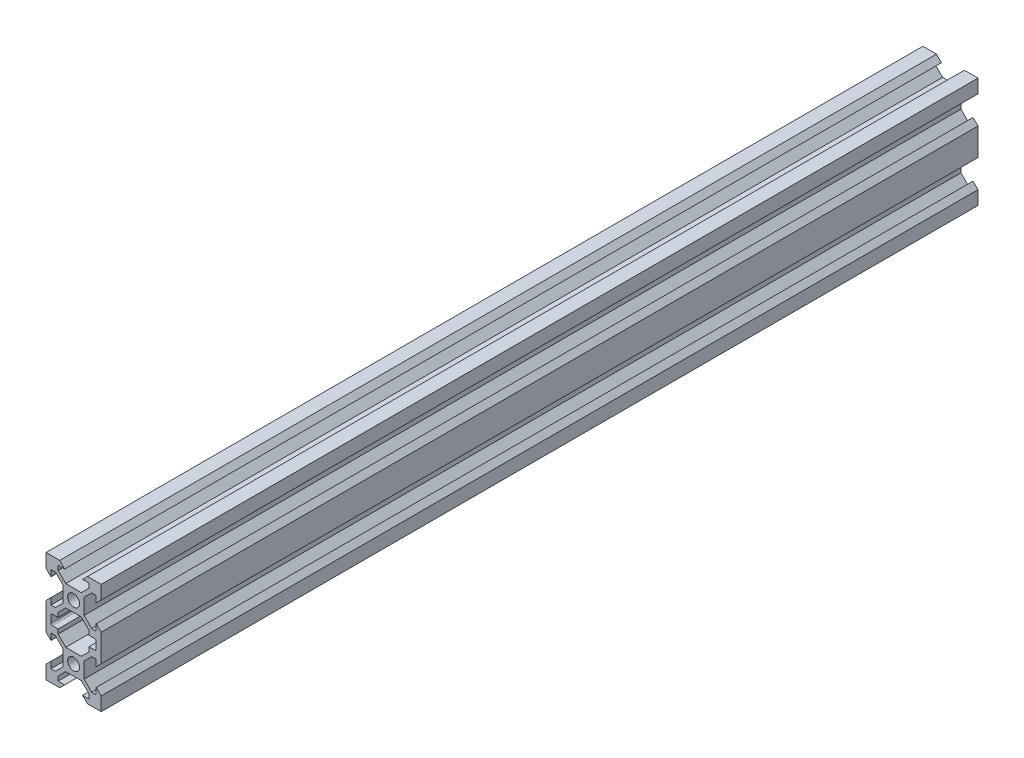
SolidWorks part; units mm, degrees
ref_plane "Alzado" through (0, 0, 0) normal (0, 0, 1) x (1, 0, 0)
ref_plane "Planta" through (0, 0, 0) normal (0, 1, 0) x (1, 0, 0)
ref_plane "Vista lateral" through (0, 0, 0) normal (1, 0, 0) x (0, 0, -1)
sketch "Croquis1" plane through (0, 0, 0) normal (0, 0, 1) x (1, 0, 0)
  line L0 (0, 0) -> (0, -20) construction
  line L2 (0, 0) -> (0, -0.5674)
  line L5 (6.175, -7.1649) -> (6.175, -12.8351)
  line L6 (7.1649, -13.825) -> (12.8351, -13.825)
  line L7 (13.825, -7.1649) -> (13.825, -12.8351)
  line L8 (7.1649, -6.175) -> (12.8351, -6.175)
  line L9 (6.175, -13.825) -> (13.825, -13.825) construction
  line L10 (13.825, -6.175) -> (13.825, -13.825) construction
  line L12 (10, -10) -> (32.1172, -10) construction
  line L13 (13.25, -18.2) -> (15.05, -20)
  line L14 (20, -20) -> (15.6, -20)
  line L15 (20, -20) -> (20, -15.6)
  line L16 (18.2, -15.6) -> (16.5899, -15.6)
  line L32 (15.6, -18.2) -> (15.6, -16.5899)
  line L33 (10, -10) -> (10, -23.2493) construction
  line L34 (4.4, -18.2) -> (4.4, -16.5899)
  line L35 (7.1649, -13.825) -> (4.4, -16.5899)
  line L36 (15.6, -18.2) -> (13.25, -18.2)
  line L38 (15.6, -20) -> (15.05, -20)
  line L40 (15.05, -20) -> (20, -20)
  line L41 (0, -20) -> (20, -20) construction
  line L42 (6.175, -12.8351) -> (3.4101, -15.6)
  line L43 (18.2, -13.25) -> (20, -15.05)
  line L44 (20, -20) -> (18.2, -20)
  line L45 (20, -20) -> (20, -15.05)
  line L48 (20, -15.05) -> (20, -20)
  line L49 (20, 0) -> (20, -20) construction
  line L50 (18.2, -15.6) -> (18.2, -13.25)
  line L51 (12.8351, -13.825) -> (15.6, -16.5899)
  line L52 (13.825, -12.8351) -> (16.5899, -15.6)
  line L53 (1.8, -15.6) -> (3.4101, -15.6)
  line L54 (1.8, -15.6) -> (1.8, -13.25)
  line L55 (1.8, -13.25) -> (0, -15.05)
  line L56 (0, 0) -> (20, 0) construction
  line L57 (0, -20) -> (0, -15.6)
  line L58 (0, -15.6) -> (0, -15.05)
  line L59 (0, -20) -> (4.4, -20)
  line L60 (0, -20) -> (4.95, -20)
  line L61 (6.75, -18.2) -> (4.95, -20)
  line L62 (4.4, -18.2) -> (6.75, -18.2)
  line L63 (1.8, -4.4) -> (3.4101, -4.4)
  line L64 (6.175, -7.1649) -> (3.4101, -4.4)
  line L65 (7.1649, -6.175) -> (4.4, -3.4101)
  line L66 (4.4, -1.8) -> (4.4, -3.4101)
  line L71 (0, 0) -> (0, -4.4)
  line L72 (0, 0) -> (0, -4.95)
  line L73 (1.8, -6.75) -> (0, -4.95)
  line L74 (1.8, -4.4) -> (1.8, -6.75)
  line L75 (15.6, -1.8) -> (15.6, -3.4101)
  line L76 (12.8351, -6.175) -> (15.6, -3.4101)
  line L77 (13.825, -7.1649) -> (16.5899, -4.4)
  line L78 (18.2, -4.4) -> (16.5899, -4.4)
  line L79 (18.2, -4.4) -> (18.2, -6.75)
  line L80 (18.2, -6.75) -> (20, -4.95)
  line L81 (20, 0) -> (20, -4.4)
  line L82 (20, -4.4) -> (20, -4.95)
  line L87 (6.175, -6.175) -> (13.825, -6.175) construction
  line L88 (6.175, -6.175) -> (6.175, -13.825) construction
  line L89 (0, 20) -> (0, 19.4326)
  line L90 (6.175, 12.8351) -> (6.175, 7.1649)
  line L91 (7.1649, 6.175) -> (12.8351, 6.175)
  line L92 (13.825, 12.8351) -> (13.825, 7.1649)
  line L93 (7.1649, 13.825) -> (12.8351, 13.825)
  line L96 (20, 0) -> (20, 4.4)
  line L97 (18.2, 4.4) -> (16.5899, 4.4)
  line L98 (15.6, 1.8) -> (15.6, 3.4101)
  line L99 (4.4, 1.8) -> (4.4, 3.4101)
  line L100 (7.1649, 6.175) -> (4.4, 3.4101)
  line L104 (6.175, 7.1649) -> (3.4101, 4.4)
  line L105 (18.2, 6.75) -> (20, 4.95)
  line L107 (20, 0) -> (20, 4.95)
  line L108 (20, 4.95) -> (20, 0)
  line L109 (18.2, 4.4) -> (18.2, 6.75)
  line L110 (12.8351, 6.175) -> (15.6, 3.4101)
  line L111 (13.825, 7.1649) -> (16.5899, 4.4)
  line L112 (1.8, 4.4) -> (3.4101, 4.4)
  line L113 (1.8, 4.4) -> (1.8, 6.75)
  line L114 (1.8, 6.75) -> (0, 4.95)
  line L115 (0, 0) -> (0, 4.4)
  line L116 (0, 4.4) -> (0, 4.95)
  line L121 (1.8, 15.6) -> (3.4101, 15.6)
  line L122 (6.175, 12.8351) -> (3.4101, 15.6)
  line L123 (7.1649, 13.825) -> (4.4, 16.5899)
  line L124 (4.4, 18.2) -> (4.4, 16.5899)
  line L125 (4.4, 18.2) -> (6.75, 18.2)
  line L126 (6.75, 18.2) -> (4.95, 20)
  line L127 (0, 20) -> (4.4, 20)
  line L128 (4.4, 20) -> (4.95, 20)
  line L129 (0, 20) -> (0, 15.6)
  line L130 (0, 20) -> (0, 15.05)
  line L131 (1.8, 13.25) -> (0, 15.05)
  line L132 (1.8, 15.6) -> (1.8, 13.25)
  line L133 (15.6, 18.2) -> (15.6, 16.5899)
  line L134 (12.8351, 13.825) -> (15.6, 16.5899)
  line L135 (13.825, 12.8351) -> (16.5899, 15.6)
  line L136 (18.2, 15.6) -> (16.5899, 15.6)
  line L137 (18.2, 15.6) -> (18.2, 13.25)
  line L138 (18.2, 13.25) -> (20, 15.05)
  line L139 (20, 20) -> (20, 15.6)
  line L140 (20, 15.6) -> (20, 15.05)
  line L141 (20, 20) -> (15.6, 20)
  line L142 (20, 20) -> (15.05, 20)
  line L143 (13.25, 18.2) -> (15.05, 20)
  line L144 (15.6, 18.2) -> (13.25, 18.2)
  line L146 (4.4, 1.8) -> (2.3, 1.8)
  line L147 (10, 10) -> (10, -3.2493) construction
  line L148 (10, 10) -> (32.1172, 10) construction
  line L150 (4.4, -1.8) -> (2.3, -1.8)
  line L151 (1.8, 1.3) -> (1.8, -1.3)
  line L152 (15.6, -1.8) -> (17.7, -1.8)
  line L154 (15.6, 1.8) -> (17.7, 1.8)
  line L155 (18.2, -1.3) -> (18.2, 1.3)
  line L156 (4.4, 1.8) -> (6.75, 1.8) [skipped]
  line L157 (6.75, 1.8) -> (4.95, 0) [skipped]
  line L158 (6.75, -1.8) -> (4.95, 0) [skipped]
  line L159 (4.4, -1.8) -> (6.75, -1.8) [skipped]
  line L160 (15.6, -1.8) -> (13.25, -1.8) [skipped]
  line L161 (13.25, -1.8) -> (15.05, 0) [skipped]
  line L162 (13.25, 1.8) -> (15.05, 0) [skipped]
  line L163 (15.6, 1.8) -> (13.25, 1.8) [skipped]
  line L164 (15.6, 0) -> (15.05, 0) [skipped]
  line L165 (4.4, 0) -> (4.95, 0) [skipped]
  line L166 (20, 0) -> (18.2, 0) [skipped]
  line L167 (18.2, 0) -> (20, 0) [skipped]
  line L168 (20, 0) -> (18.2, 0) [skipped]
  line L169 (20, 0) -> (18.2, 0) [skipped]
  line L170 (20, 0) -> (18.2, 0) [skipped]
  line L171 (0, 0) -> (1.8, 0) [skipped]
  line L172 (0, 0) -> (1.8, 0) [skipped]
  line L173 (0, 0) -> (1.8, 0) [skipped]
  circle A0 centre (10, -10) radius 2.15
  circle A1 centre (10, 10) radius 2.15
  arc A2 (17.7, 1.8) -> (18.2, 1.3) centre (17.7, 1.3) cw
  arc A3 (17.7, -1.8) -> (18.2, -1.3) centre (17.7, -1.3) ccw
  arc A4 (2.3, -1.8) -> (1.8, -1.3) centre (2.3, -1.3) cw
  arc A5 (2.3, 1.8) -> (1.8, 1.3) centre (2.3, 1.3) ccw
  point P69 (10, -10)
  point P128 (10, 10)
  dimension "D3" = 4.3
  dimension "D5" = 0.5
  dimension "D2" = 4
  dimension "D4" = 2
  dimension "D11" = 4.4
  dimension "D15" = 4.4
  dimension "D16" = 6.75
extrude "Saliente-Extruir1" add sketch "Croquis1" along normal blind 318 contours L144 L133 L134 L93 L123 L124 L125 L126 L128 L127 L89 L129 L130 L131 L132 L121 L122 L90 L104 L112 L113 L114 L116 L115 L2 L71 L72 L73 L74 L63 L64 L5 L42 L53 L54 L55 L58 L57 L59 L60 L61 L62 L34 L35 L6 L51 L32 L36 L13 L38 L40
